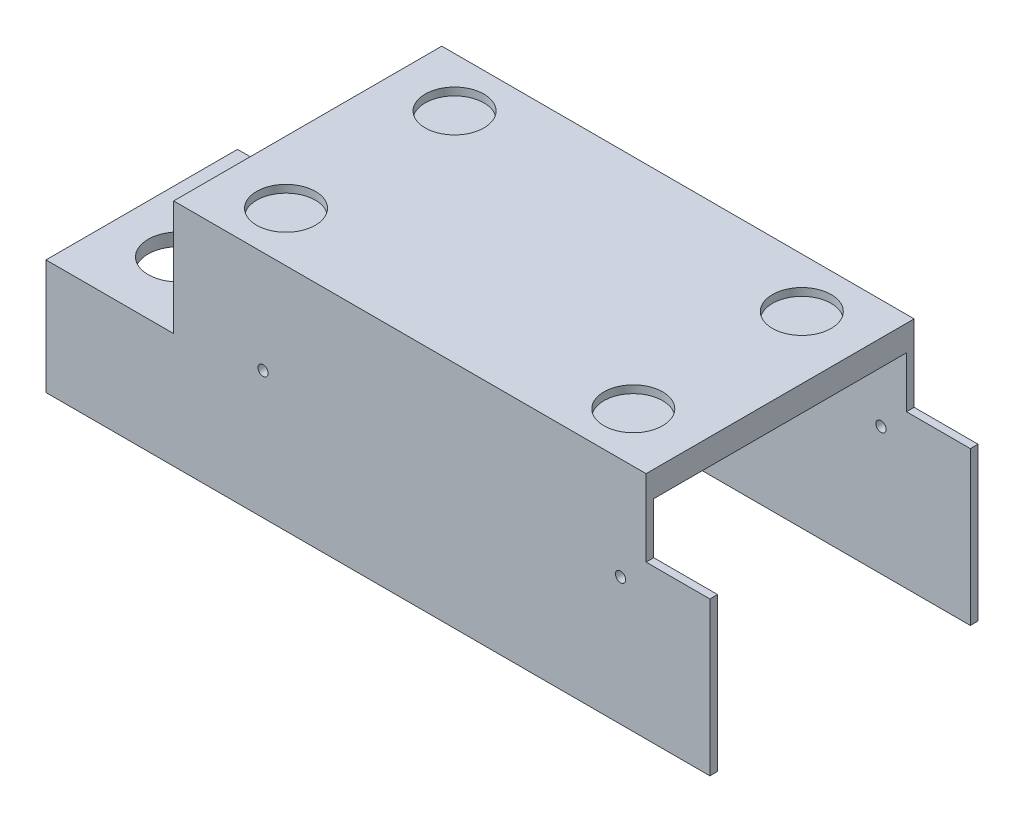
SolidWorks part; units mm, degrees
material "PMMA"
ref_plane "前视基准面" through (0, 0, 0) normal (0, 0, 1) x (1, 0, 0)
ref_plane "上视基准面" through (0, 0, 0) normal (0, 1, 0) x (1, 0, 0)
ref_plane "右视基准面" through (0, 0, 0) normal (1, 0, 0) x (0, 0, -1)
other "Configuration Table"
sketch "草图2" plane through (0, 0, 0) normal (0, 1, 0) x (1, 0, 0)
  line L1 (-105, 52.5) -> (105, 52.5)
  line L2 (-105, 52.5) -> (-105, -52.5)
  line L3 (-105, -52.5) -> (105, -52.5)
  line L4 (105, 52.5) -> (105, -52.5)
  line L5 (-105, 52.5) -> (105, -52.5) construction
  line L6 (-105, -52.5) -> (105, 52.5) construction
  point P0 (0, 0)
  dimension "D1" = 210
  dimension "D2" = 105
extrude "凸台-拉伸1" add sketch "草图2" along normal blind 90
sketch "草图4" plane through (0, 90, 0) normal (0, 1, 0) x (1, 0, 0)
  line L3 (-95, -47.5) -> (70, -47.5)
  line L4 (70, 47.5) -> (70, -47.5)
  line L5 (-105, -52.5) -> (105, -52.5) construction
  circle A0 centre (-80.5, 33) radius 11.5
  circle A1 centre (-80.5, -33) radius 11.5
  circle A2 centre (55.5, 33) radius 11.5
  circle A3 centre (55.5, -33) radius 11.5
  dimension "D5" = 23
  dimension "D6" = 23
  dimension "D11" = 23
  dimension "D13" = 14.5
  dimension "D2" = 5
  dimension "D10" = 14.5
sketch "草图5" plane through (105, 0, 0) normal (1, 0, 0) x (0, 0, -1)
  line L0 (-52.5, 0) -> (52.5, 0) construction
  line L1 (-49.5, 0) -> (49.5, 0)
  line L2 (-49.5, 0) -> (-49.5, 80)
  line L3 (-49.5, 80) -> (49.5, 80)
  line L4 (49.5, 0) -> (49.5, 80)
  line L5 (-52.5, 90) -> (-52.5, 0) construction
  line L6 (52.5, 90) -> (52.5, 0) construction
  line L7 (-52.5, 90) -> (52.5, 90) construction
  dimension "D1" = 3
  dimension "D2" = 3
  dimension "D3" = 10
extrude "切除-拉伸2" cut sketch "草图5" against normal blind 200
sketch "草图6" plane through (-105, 0, 0) normal (-1, 0, 0) x (0, 0, 1)
  line L2 (52.5, 0) -> (-22.5, 0)
  line L3 (52.5, 0) -> (52.5, 45)
  line L4 (52.5, 45) -> (-22.5, 45)
  line L5 (-22.5, 0) -> (-22.5, 45)
  dimension "D1" = 45
  dimension "D2" = 75
extrude "凸台-拉伸2" add sketch "草图6" along normal blind 50
sketch "草图7" plane through (-155, 0, 0) normal (-1, 0, 0) x (0, 0, 1)
  line L0 (-22.5, 0) -> (52.5, 0) construction
  line L1 (-19.5, 40) -> (49.5, 40)
  line L2 (-19.5, 40) -> (-19.5, 0)
  line L3 (-19.5, 0) -> (49.5, 0)
  line L4 (49.5, 40) -> (49.5, 0)
  line L5 (-22.5, 45) -> (-22.5, 0) construction
  line L6 (52.5, 0) -> (52.5, 45) construction
  line L7 (52.5, 45) -> (-22.5, 45) construction
  dimension "D1" = 3
  dimension "D2" = 3
  dimension "D3" = 5
extrude "切除-拉伸3" cut sketch "草图7" against normal through all
sketch "草图8" plane through (0, 45, 0) normal (0, 1, 0) x (1, 0, 0)
  line L0 (-155, -52.5) -> (-155, 22.5) construction
  line L1 (-155, -52.5) -> (-105, -52.5) construction
  circle A0 centre (-130, -25.5) radius 12
  dimension "D3" = 24
  dimension "D1" = 25
  dimension "D2" = 27
extrude "切除-拉伸4" cut sketch "草图8" against normal through all
sketch "草图9" plane through (0, 0, 52.5) normal (0, 0, 1) x (1, 0, 0)
  line L0 (-105, 90) -> (-105, 45) construction
  line L1 (-155, 0) -> (105, 0) construction
  line L3 (-155, 0) -> (-155, 45) construction
  circle A0 centre (-70, 50) radius 2
  circle A1 centre (70, 50) radius 2
  dimension "D3" = 4
  dimension "D4" = 4
  dimension "D5" = 225
  dimension "D1" = 35
  dimension "D2" = 50
extrude "切除-拉伸5" cut sketch "草图9" against normal through all
sketch "草图11" plane through (0, 90, 0) normal (0, 1, 0) x (1, 0, 0)
  line L0 (-105, -52.5) -> (105, -52.5) construction
  line L1 (105, 52.5) -> (80, 52.5)
  line L2 (105, 52.5) -> (105, -52.5)
  line L3 (105, -52.5) -> (80, -52.5)
  line L4 (80, 52.5) -> (80, -52.5)
  dimension "D1" = 25
extrude "切除-拉伸6" cut sketch "草图11" against normal blind 30
extrude "切除-拉伸8" cut sketch "草图4" against normal blind 3 contours A0 | A2 | A1 | A3
ref_plane "基准面1" through (105, 0, 49.5) normal (1, 0, 0) x (0, 0, -1)
